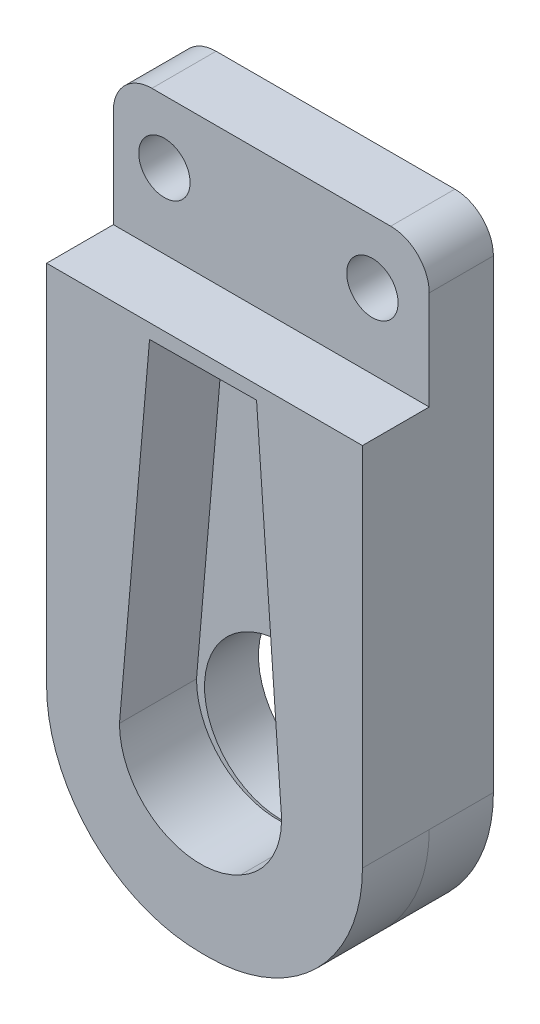
SolidWorks part; units mm, degrees
ref_plane "Front Plane" through (0, 0, 0) normal (0, 0, 1) x (1, 0, 0)
ref_plane "Top Plane" through (0, 0, 0) normal (0, 1, 0) x (1, 0, 0)
ref_plane "Right Plane" through (0, 0, 0) normal (1, 0, 0) x (0, 0, -1)
other "Graphic1"
ref_plane "Plane2" through (0, 0, 10) normal (0, 0, 1) x (1, 0, 0)
sketch "Sketch2" plane through (0, 0, 10) normal (0, 0, 1) x (1, 0, 0)
  line L1 (-326.0372, 240.3637) -> (-313.7372, 240.3637)
  line L2 (-326.0372, 240.3637) -> (-326.0372, 214.7637)
  line L3 (-326.0372, 214.7637) -> (-313.7372, 214.7637)
  line L4 (-313.7372, 240.3637) -> (-313.7372, 214.7637)
  dimension "D1" = 12.3
  dimension "D2" = 25.6
extrude "Boss-Extrude1" add sketch "Sketch2" along normal blind 2.5
fillet "Fillet1" radius 6 2 edges at (-313.7372, 214.7637, 11.25) (-326.0372, 214.7637, 11.25)
fillet "Fillet2" radius 1.5 2 edges at (-326.0372, 240.3637, 11.25) (-313.7372, 240.3637, 11.25)
sketch "Sketch3" plane through (0, 0, 12.5) normal (0, 0, 1) x (1, 0, 0)
  circle A0 centre (-324.0491, 237.9223) radius 1
  circle A1 centre (-315.9491, 237.9223) radius 1
  dimension "D1" = 2
  dimension "D2" = 2
  dimension "D3" = 8.1
extrude "Cut-Extrude1" cut sketch "Sketch3" against normal blind 3.5
ref_plane "Plane3" through (0, 0, 12.5) normal (0, 0, 1) x (1, 0, 0)
sketch "Sketch4" plane through (0, 0, 12.5) normal (0, 0, 1) x (1, 0, 0)
  line L0 (-326.0372, 238.8637) -> (-326.0372, 220.7637) construction
  line L1 (-326.0372, 235.0154) -> (-313.7372, 235.0154)
  line L2 (-326.0372, 235.0154) -> (-326.0372, 214.7637)
  line L3 (-326.0372, 214.7637) -> (-313.7372, 214.7637)
  line L4 (-313.7372, 235.0154) -> (-313.7372, 214.7637)
extrude "Boss-Extrude2" add sketch "Sketch4" along normal blind 2.6
fillet "Fillet3" radius 6 2 edges at (-313.7372, 214.7637, 13.8) (-326.0372, 214.7637, 13.8)
sketch "Sketch5" plane through (0, 0, 15.1) normal (0, 0, 1) x (1, 0, 0)
  line L0 (-319.8872, 235.0154) -> (-319.8872, 211.9352) construction
  line L1 (-313.7372, 235.0154) -> (-326.0372, 235.0154) construction
  circle A0 centre (-319.8872, 220.8121) radius 3
  dimension "D1" = 6
extrude "Cut-Extrude2" cut sketch "Sketch5" against normal through all
sketch "Sketch6" plane through (0, 0, 15.1) normal (0, 0, 1) x (1, 0, 0)
  line L0 (-322.0282, 234.4487) -> (-317.8616, 234.486)
  line L1 (-317.8616, 234.486) -> (-316.8883, 220.8919)
  line L2 (-322.0282, 234.4487) -> (-323.1992, 220.915)
  circle A0 centre (-319.8872, 220.8121) radius 3 construction
  arc A1 (-323.1992, 220.915) -> (-316.8883, 220.8919) centre (-320.0438, 220.9035) ccw
extrude "Cut-Extrude3" cut sketch "Sketch6" against normal blind 3
